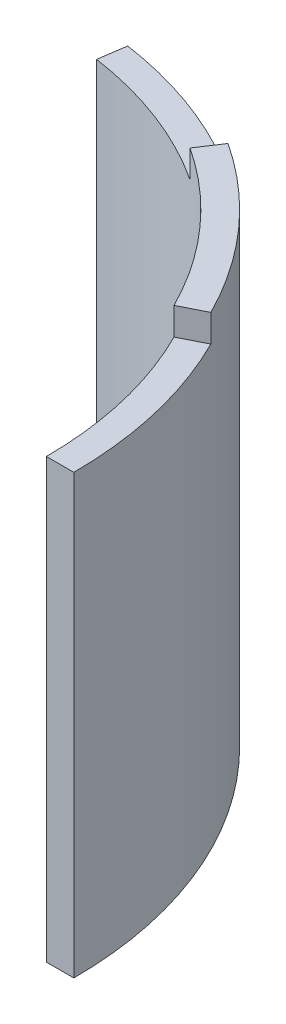
SolidWorks part; units mm, degrees
ref_plane "Front Plane" through (0, 0, 0) normal (0, 0, 1) x (1, 0, 0)
ref_plane "Top Plane" through (0, 0, 0) normal (0, 1, 0) x (1, 0, 0)
ref_plane "Right Plane" through (0, 0, 0) normal (1, 0, 0) x (0, 0, -1)
sketch "Sketch1" plane through (0, 0, 0) normal (0, 1, 0) x (1, 0, 0)
  line L0 (6.278, 42.7212) -> (6.7397, 45.8624)
  line L1 (43.18, 0) -> (46.355, 0)
  arc A0 (43.18, 0) -> (6.278, 42.7212) centre (0, 0) ccw
  arc A1 (46.355, 0) -> (6.7397, 45.8624) centre (0, 0) ccw
  point P6 (0, 0)
  point P7 (47.5166, 0.8327)
  dimension "D1" = 3.175
  dimension "D2" = 43.18
  dimension "D3" = 81.64
extrude "Boss-Extrude1" add sketch "Sketch1" along normal mid plane 50.7
sketch "Sketch4" plane through (0, 25.35, 0) normal (0, 1, 0) x (1, 0, 0)
  line L3 (41.434, 20.7848) -> (38.5961, 19.3612)
  line L4 (25.4905, 38.7172) -> (23.7446, 36.0653)
  line L6 (6.7397, 45.8624) -> (6.278, 42.7212) construction
  arc A0 (41.434, 20.7848) -> (25.4905, 38.7172) centre (0, 0) ccw
  arc A1 (46.355, 0) -> (6.7397, 45.8624) centre (0, 0) ccw construction
  arc A2 (38.5961, 19.3612) -> (23.7446, 36.0653) centre (0, 0) ccw
  arc A3 (43.18, 0) -> (6.278, 42.7212) centre (0, 0) ccw construction
  point P12 (28.9308, 32.0549)
  point P20 (0, 0)
  dimension "D1" = 25
  dimension "D2" = 30
extrude "Boss-Extrude2" add sketch "Sketch4" along normal blind 3.175
